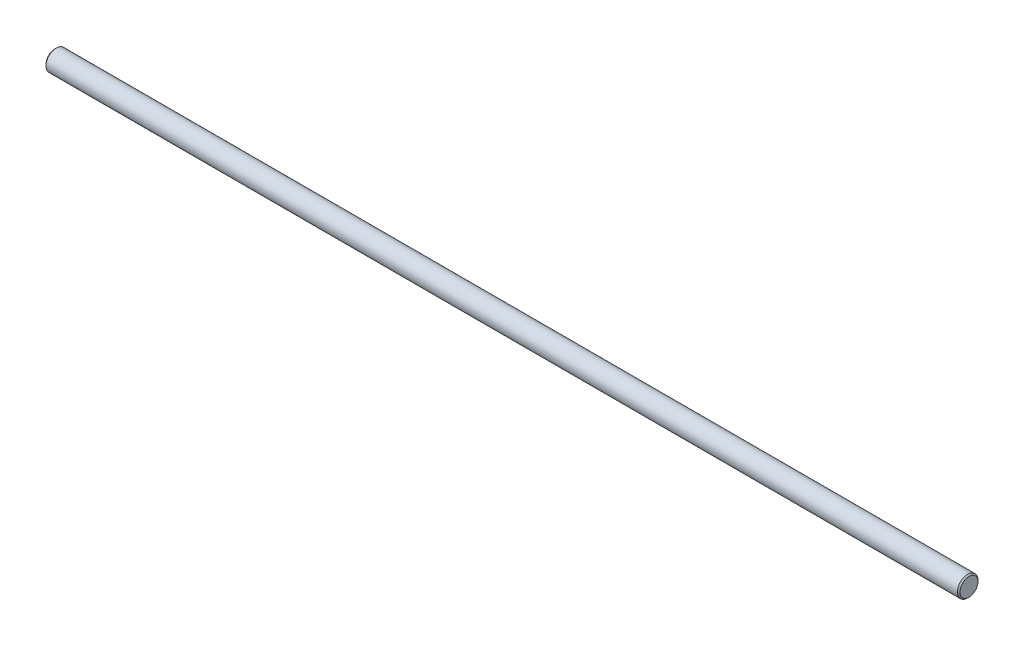
SolidWorks part; units mm, degrees
ref_plane "Front Plane" through (0, 0, 0) normal (0, 0, 1) x (1, 0, 0)
ref_plane "Top Plane" through (0, 0, 0) normal (0, 1, 0) x (1, 0, 0)
ref_plane "Right Plane" through (0, 0, 0) normal (1, 0, 0) x (0, 0, -1)
sketch "Sketch1" plane through (0, 0, 0) normal (0, 0, 1) x (1, 0, 0)
  line L0 (0, 3.5) -> (0, 0)
  line L1 (0, 0) -> (355, 0)
  line L2 (355, 0) -> (355, 3.5)
  line L3 (355, 3.5) -> (354.5, 4)
  line L4 (354.5, 4) -> (0.5, 4)
  line L5 (0.5, 4) -> (0, 3.5)
  line L6 (0, 0) -> (355, 0) construction
revolve "Revolve1" add sketch "Sketch1" angle 360 about L6
